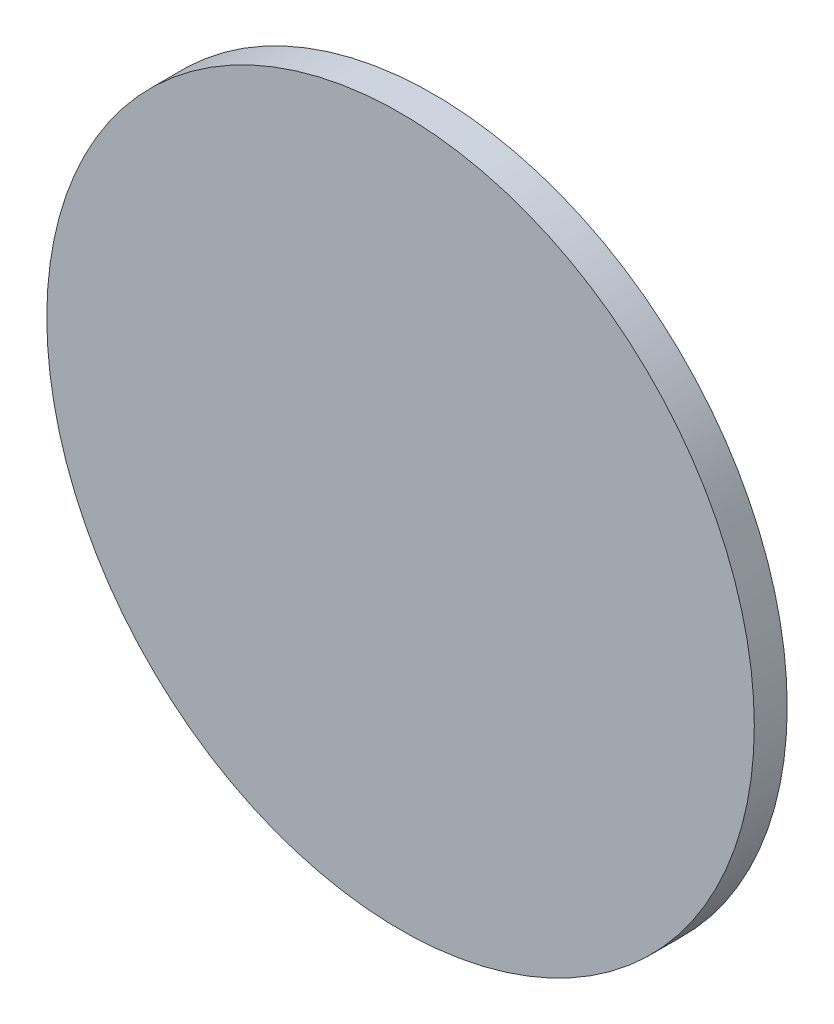
SolidWorks part; units mm, degrees
ref_plane "Front Plane" through (0, 0, 0) normal (0, 0, 1) x (1, 0, 0)
ref_plane "Top Plane" through (0, 0, 0) normal (0, 1, 0) x (1, 0, 0)
ref_plane "Right Plane" through (0, 0, 0) normal (1, 0, 0) x (0, 0, -1)
sketch "Sketch3" plane through (0, 0, 0) normal (0, 0, 1) x (1, 0, 0)
  circle A0 centre (0, 0) radius 107.5
  dimension "D1" = 215
extrude "Boss-Extrude1" add sketch "Sketch3" along normal blind 10
